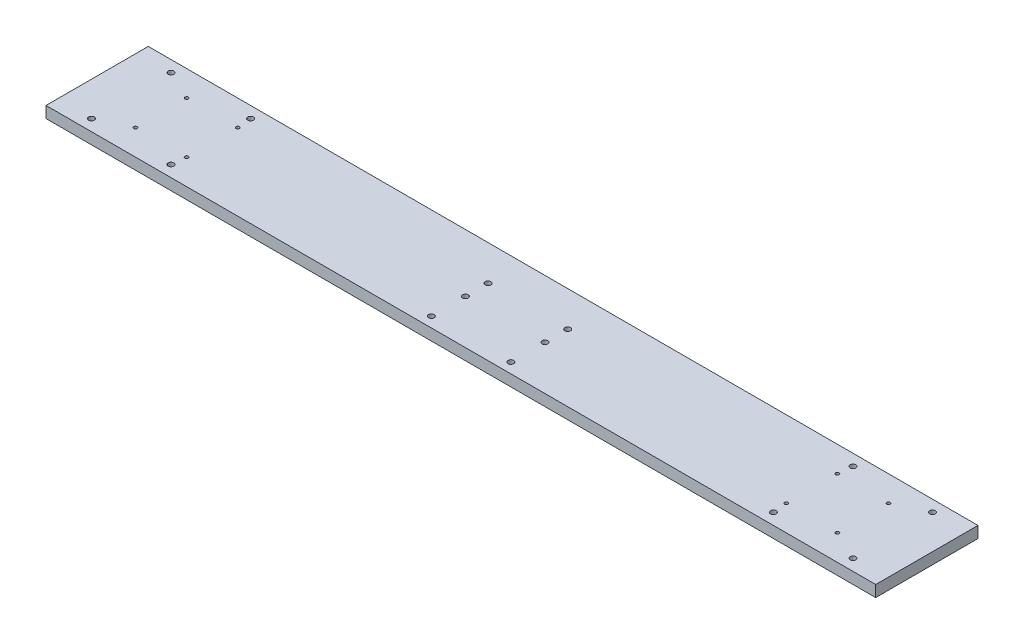
SolidWorks part; units mm, degrees
ref_plane "前视基准面" through (0, 0, 0) normal (0, 0, 1) x (1, 0, 0)
ref_plane "上视基准面" through (0, 0, 0) normal (0, 1, 0) x (1, 0, 0)
ref_plane "右视基准面" through (0, 0, 0) normal (1, 0, 0) x (0, 0, -1)
other "Configuration Table"
sketch "草图1" plane through (0, 0, 0) normal (0, 1, 0) x (1, 0, 0)
  line L1 (0, 0) -> (240, 0)
  line L2 (0, 0) -> (0, -90)
  line L3 (0, -90) -> (240, -90)
  line L4 (240, 0) -> (240, -90)
  dimension "D1" = 240
  dimension "D2" = 90
extrude "凸台-拉伸1" add sketch "草图1" along normal blind 4
sketch "草图2" plane through (0, 4, 0) normal (0, 1, 0) x (1, 0, 0)
  line L0 (0, -90) -> (240, -90) construction
  line L1 (35, 0) -> (205, 0)
  line L2 (35, 0) -> (35, -90)
  line L3 (35, -90) -> (205, -90)
  line L4 (205, 0) -> (205, -90)
  line L5 (35, 0) -> (205, -90) construction
  line L6 (35, -90) -> (205, 0) construction
  line L7 (240, 0) -> (0, 0) construction
  line L8 (240, -90) -> (240, 0) construction
  line L9 (0, 0) -> (0, -90) construction
  point P0 (120, -45)
  dimension "D1" = 170
  dimension "D2" = 35
  dimension "D3" = 35
extrude "凸台-拉伸2" add sketch "草图2" along normal blind 6
sketch "草图4" plane through (0, 0, 0) normal (0, -1, 0) x (1, 0, 0)
  line L0 (120, 112.4585) -> (120, -34.2891) construction
  line L7 (85, 90) -> (85, 0) construction
  line L9 (155, 90) -> (155, 0) construction
  circle A0 centre (85, 81) radius 2.5
  circle A1 centre (155, 81) radius 2.5
  circle A2 centre (85, 31) radius 2.5
  circle A3 centre (155, 31) radius 2.5
  circle A4 centre (85, 51) radius 2.5
  circle A5 centre (155, 51) radius 2.5
  dimension "D3" = 5
  dimension "D4" = 5
  dimension "D5" = 5
  dimension "D6" = 5
  dimension "D9" = 50
  dimension "D10" = 50
  dimension "D11" = 5
  dimension "D12" = 5
  dimension "D13" = 20
  dimension "D14" = 20
  dimension "D1" = 35
  dimension "D2" = 35
extrude "切除-拉伸5" cut sketch "草图4" against normal through all
sketch "草图5" plane through (205, 0, 0) normal (1, 0, 0) x (0, 0, -1)
  line L1 (-90, 10) -> (0, 10)
  line L2 (-90, 10) -> (-90, 0)
  line L3 (-90, 0) -> (0, 0)
  line L4 (0, 10) -> (0, 0)
extrude "凸台-拉伸3" add sketch "草图5" along normal blind 250
sketch "草图6" plane through (35, 0, 0) normal (-1, 0, 0) x (0, 0, 1)
  line L1 (0, 10) -> (90, 10)
  line L2 (0, 10) -> (0, 0)
  line L3 (0, 0) -> (90, 0)
  line L4 (90, 10) -> (90, 0)
extrude "凸台-拉伸4" add sketch "草图6" along normal blind 250
sketch "草图7" plane through (0, 10, 0) normal (0, 1, 0) x (1, 0, 0)
  line L0 (-215, -90) -> (-215, 0) construction
  line L1 (-188.76, -22.5) -> (-143.76, -22.5) construction
  line L2 (-188.76, -22.5) -> (-188.76, -67.5) construction
  line L3 (-188.76, -67.5) -> (-143.76, -67.5) construction
  line L4 (-143.76, -22.5) -> (-143.76, -67.5) construction
  line L5 (455, 0) -> (-215, 0) construction
  line L6 (120, -90) -> (120, 122.0967) construction
  line L7 (-215, -90) -> (455, -90) construction
  line L8 (383.76, -22.5) -> (383.76, -67.5) construction
  line L9 (428.76, -67.5) -> (383.76, -67.5) construction
  line L10 (428.76, -22.5) -> (428.76, -67.5) construction
  line L11 (428.76, -22.5) -> (383.76, -22.5) construction
  circle A0 centre (-188.76, -22.5) radius 1.5
  circle A1 centre (-188.76, -67.5) radius 1.5
  circle A2 centre (-143.76, -67.5) radius 1.5
  circle A3 centre (-143.76, -22.5) radius 1.5
  circle A4 centre (383.76, -22.5) radius 1.5
  circle A5 centre (383.76, -67.5) radius 1.5
  circle A6 centre (428.76, -67.5) radius 1.5
  circle A7 centre (428.76, -22.5) radius 1.5
  dimension "D5" = 3
  dimension "D6" = 3
  dimension "D7" = 3
  dimension "D8" = 3
  dimension "D1" = 26.24
  dimension "D2" = 22.5
  dimension "D3" = 45
  dimension "D4" = 45
extrude "切除-拉伸7" cut sketch "草图7" against normal blind 520
sketch "草图8" plane through (0, 0, 0) normal (0, -1, 0) x (1, 0, 0)
  circle A0 centre (-188.76, 67.5) radius 3.5
  circle A1 centre (-143.76, 67.5) radius 3.5
  circle A2 centre (-143.76, 22.5) radius 3.5
  circle A3 centre (-188.76, 22.5) radius 3.5
  circle A4 centre (383.76, 67.5) radius 3.5
  circle A5 centre (428.76, 67.5) radius 3.5
  circle A6 centre (383.76, 22.5) radius 3.5
  circle A7 centre (428.76, 22.5) radius 3.5
  dimension "D1" = 7
  dimension "D2" = 7
  dimension "D3" = 7
  dimension "D4" = 7
  dimension "D5" = 7
  dimension "D6" = 7
  dimension "D7" = 7
  dimension "D8" = 7
extrude "切除-拉伸8" cut sketch "草图8" against normal blind 5
sketch "草图11" plane through (-215, 0, 0) normal (-1, 0, 0) x (0, 0, 1)
  line L4 (0, 10) -> (0, 0)
  line L5 (0, 0) -> (90, 0)
  line L6 (90, 0) -> (90, 10)
  line L7 (90, 10) -> (0, 10)
  line L8 (0, 10) -> (0, 0)
  line L9 (0, 0) -> (90, 0)
  line L10 (90, 0) -> (90, 10)
  line L11 (90, 10) -> (0, 10)
  dimension "D1" = 0
extrude "凸台-拉伸5" add sketch "草图11" along normal blind 30
sketch "草图12" plane through (455, 0, 0) normal (1, 0, 0) x (0, 0, -1)
  line L4 (-90, 10) -> (-90, 0)
  line L5 (-90, 0) -> (0, 0)
  line L6 (0, 0) -> (0, 10)
  line L7 (0, 10) -> (-90, 10)
  line L8 (-90, 10) -> (-90, 0)
  line L9 (-90, 0) -> (0, 0)
  line L10 (0, 0) -> (0, 10)
  line L11 (0, 10) -> (-90, 10)
  dimension "D1" = 0
extrude "凸台-拉伸6" add sketch "草图12" along normal blind 30
sketch "草图14" plane through (0, 10, 0) normal (0, 1, 0) x (1, 0, 0)
  line L1 (-215, -10) -> (-145, -10) construction
  line L2 (-215, -10) -> (-215, -80) construction
  line L3 (-215, -80) -> (-145, -80) construction
  line L4 (-145, -10) -> (-145, -80) construction
  line L5 (485, 0) -> (-245, 0) construction
  line L6 (-180, -10) -> (-180, -80) construction
  line L7 (120, 0) -> (120, -201.9384) construction
  line L8 (420, -10) -> (420, -80) construction
  line L9 (385, -10) -> (385, -80) construction
  line L10 (455, -80) -> (385, -80) construction
  line L11 (455, -10) -> (455, -80) construction
  line L12 (455, -10) -> (385, -10) construction
  circle A0 centre (-215, -10) radius 2.5
  circle A1 centre (-215, -80) radius 2.5
  circle A2 centre (-145, -80) radius 2.5
  circle A3 centre (-145, -10) radius 2.5
  circle A4 centre (385, -10) radius 2.5
  circle A5 centre (385, -80) radius 2.5
  circle A6 centre (455, -80) radius 2.5
  circle A7 centre (455, -10) radius 2.5
  dimension "D5" = 5
  dimension "D6" = 5
  dimension "D7" = 5
  dimension "D8" = 5
  dimension "D1" = 70
  dimension "D2" = 70
  dimension "D3" = 10
  dimension "D4" = 300
extrude "切除-拉伸9" cut sketch "草图14" against normal blind 30
